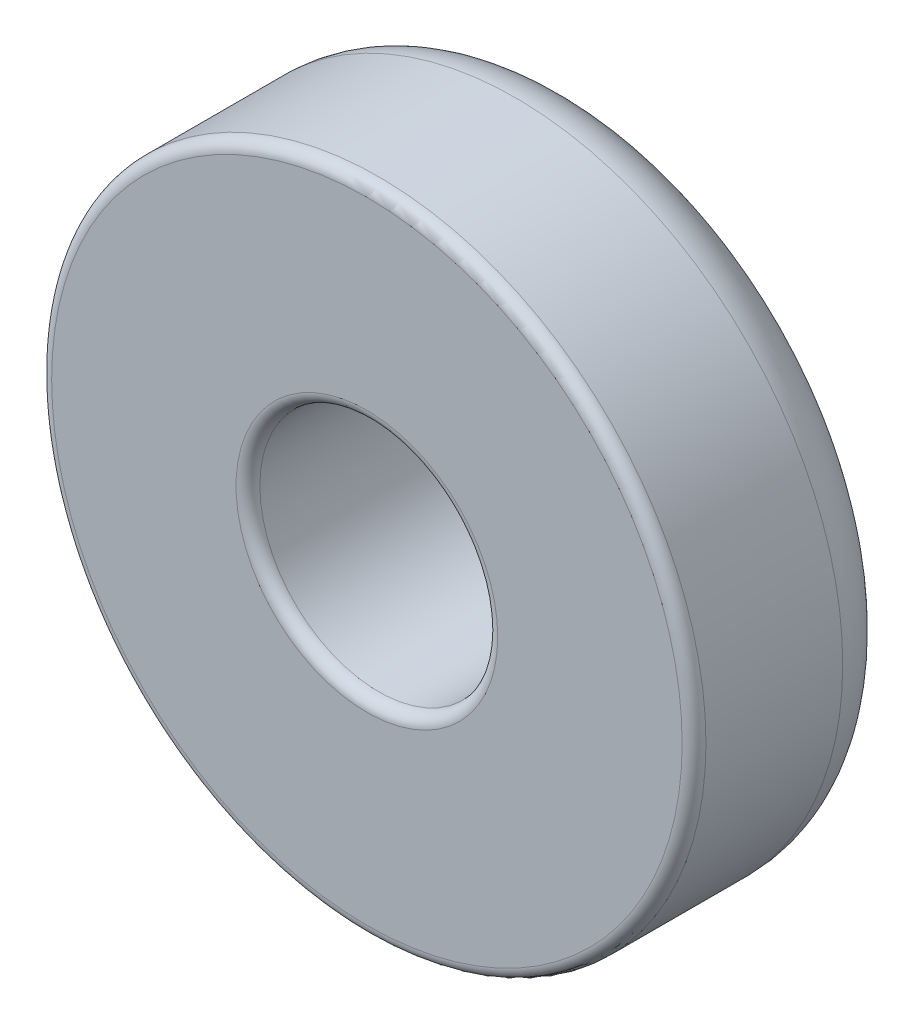
SolidWorks part; units mm, degrees
ref_plane "Front Plane" through (0, 0, 0) normal (0, 0, 1) x (1, 0, 0)
ref_plane "Top Plane" through (0, 0, 0) normal (0, 1, 0) x (1, 0, 0)
ref_plane "Right Plane" through (0, 0, 0) normal (1, 0, 0) x (0, 0, -1)
sketch "Sketch1" plane through (0, 0, 0) normal (0, 0, 1) x (1, 0, 0)
  circle A0 centre (0, 0) radius 1
  dimension "D1" = 2
extrude "Extrude-Thin1" add sketch "Sketch1" along normal blind 1.75 thin
fillet "Fillet1" radius 0.1 3 edges at (2.75, 0, 1.75) (1, 0, 0) (1, 0, 1.75)
fillet "Fillet2" radius 0.5 1 edges at (2.75, 0, 0)
scale "Scale1" scale about origin uniform scaling yes scale factor 0.445
